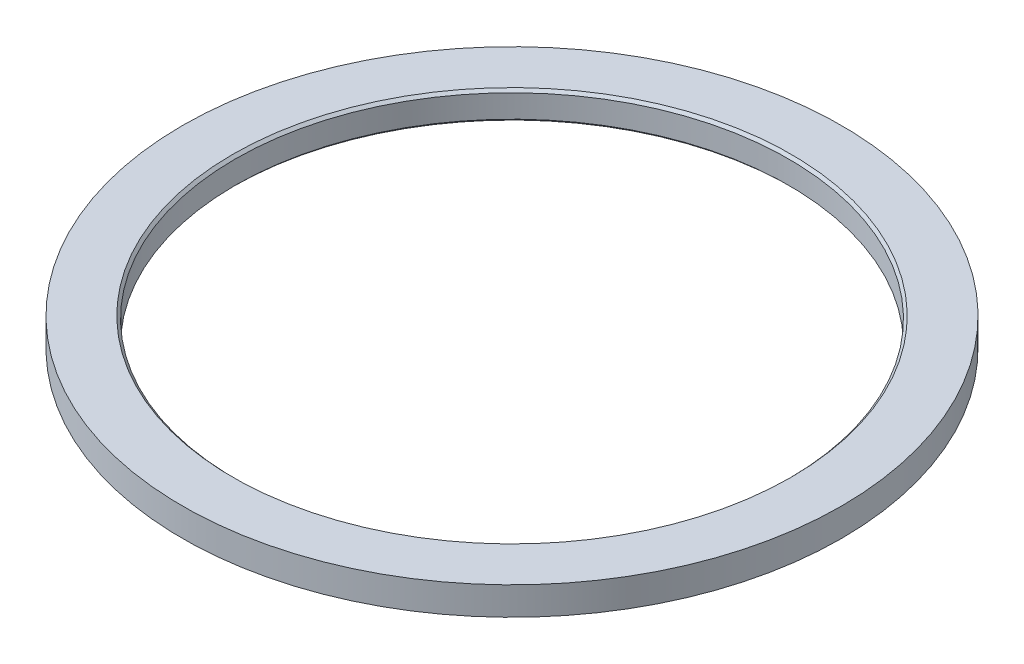
SolidWorks part; units mm, degrees
ref_plane "Front Plane" through (0, 0, 0) normal (0, 0, 1) x (1, 0, 0)
ref_plane "Top Plane" through (0, 0, 0) normal (0, 1, 0) x (1, 0, 0)
ref_plane "Right Plane" through (0, 0, 0) normal (1, 0, 0) x (0, 0, -1)
sketch "Sketch1" plane through (0, 0, 0) normal (0, 0, 1) x (1, 0, 0)
  line L0 (37.5, 3.2) -> (31.8, 3.2)
  line L1 (31.8, 3.2) -> (31.5, 2.9)
  line L2 (31.5, 2.9) -> (31.5, 0.3)
  line L3 (31.5, 0.3) -> (31.8, 0)
  line L4 (31.8, 0) -> (37.5, 0)
  line L5 (37.5, 0) -> (37.5, 3.2)
  line L6 (0, 3.2) -> (0, 0) construction
revolve "Revolve1" add sketch "Sketch1" angle 360 about L6
